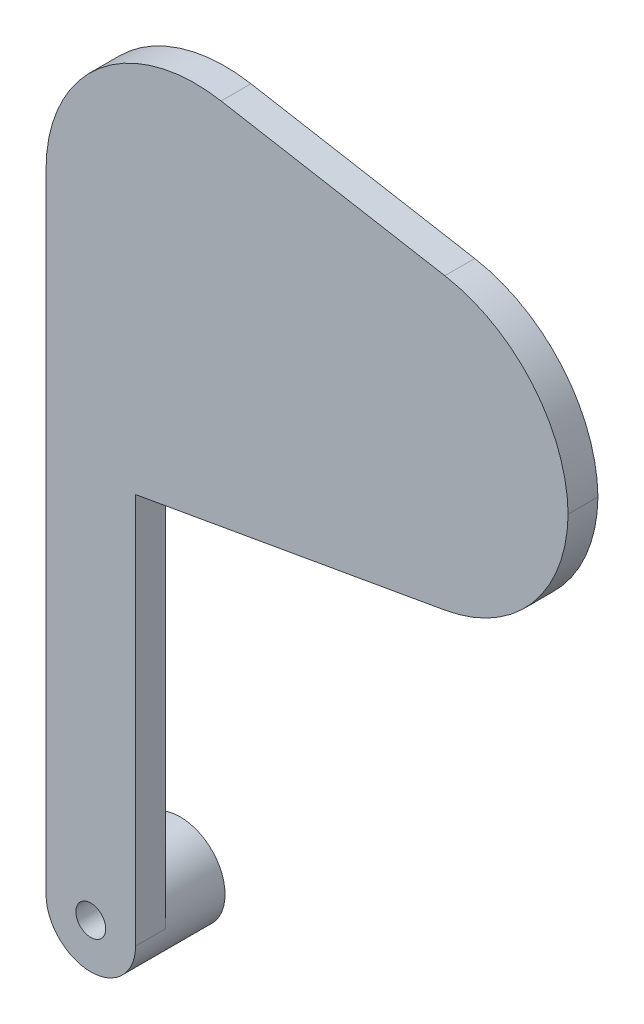
SolidWorks part; units mm, degrees
ref_plane "Front Plane" through (0, 0, 0) normal (0, 0, 1) x (1, 0, 0)
ref_plane "Top Plane" through (0, 0, 0) normal (0, 1, 0) x (1, 0, 0)
ref_plane "Right Plane" through (0, 0, 0) normal (1, 0, 0) x (0, 0, -1)
sketch "Sketch1" plane through (0, 0, 0) normal (0, 0, 1) x (1, 0, 0)
  line L0 (0, 0) -> (0, 42.0825)
  line L1 (11.7365, 51.9305) -> (26.7365, 49.2856)
  line L2 (35, 39.4376) -> (35, 39.7194)
  line L3 (26.7365, 29.8713) -> (6, 26.2149)
  line L4 (6, 26.2149) -> (6, 0)
  arc A0 (0, 0) -> (6, 0) centre (3, 0) ccw
  arc A1 (0, 42.0825) -> (11.7365, 51.9305) centre (10, 42.0825) cw
  arc A2 (35, 39.7194) -> (26.7365, 29.8713) centre (25, 39.7194) cw
  arc A3 (26.7365, 49.2856) -> (35, 39.4376) centre (25, 39.4376) cw
  point P10 (0, 54)
  point P15 (35, 47.8286)
  dimension "D6" = 10
  dimension "D1" = 54
  dimension "D2" = 80
  dimension "D3" = 35
  dimension "D4" = 100
  dimension "D5" = 6
extrude "Boss-Extrude1" add sketch "Sketch1" along normal blind 2 contours A3 L1 A1 L0 A0 L4 L3 A2
sketch "Sketch2" plane through (0, 0, 2) normal (0, 0, 1) x (1, 0, 0)
  circle A0 centre (3, 0) radius 3
  dimension "D1" = 6
extrude "Boss-Extrude2" add sketch "Sketch2" against normal blind 6
sketch "Sketch3" plane through (0, 0, -4) normal (0, 0, -1) x (-1, 0, 0)
  circle A0 centre (-3, 0) radius 2.5
  circle A1 centre (-3, 0) radius 3 construction
  dimension "D1" = 5
  dimension "D2" = 0
extrude "Cut-Extrude1" cut sketch "Sketch3" against normal blind 4
sketch "Sketch4" plane through (0, 0, 0) normal (0, 0, -1) x (-1, 0, 0)
  circle A0 centre (-3, 0) radius 1
  dimension "D1" = 2
extrude "Cut-Extrude2" cut sketch "Sketch4" against normal blind 2
